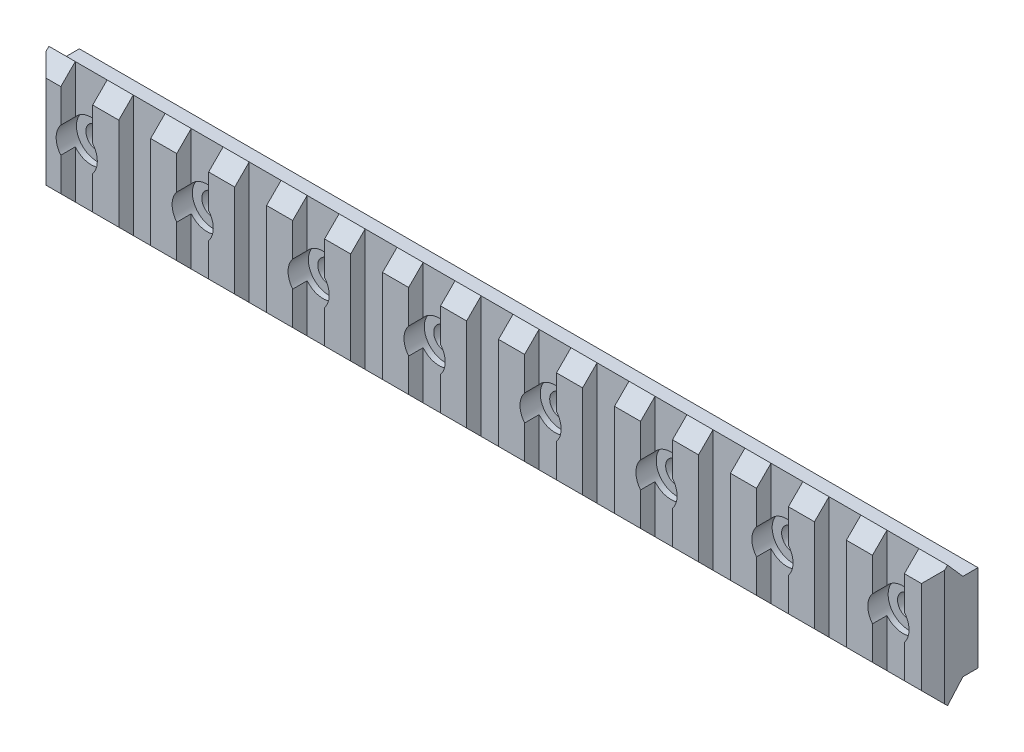
SolidWorks part; units mm, degrees
ref_plane "정면" through (0, 0, 0) normal (0, 0, 1) x (1, 0, 0)
ref_plane "윗면" through (0, 0, 0) normal (0, 1, 0) x (1, 0, 0)
ref_plane "우측면" through (0, 0, 0) normal (1, 0, 0) x (0, 0, -1)
sketch "스케치4" plane through (0, 0, 0) normal (1, 0, 0) x (0, 0, -1)
  line L0 (0, 7.5) -> (0, -7.5)
  line L1 (0, -7.5) -> (-2.6, -7.5)
  line L2 (-2.6, -7.5) -> (-5.25, -10.5)
  line L3 (-5.25, -10.5) -> (-7.75, -8)
  line L4 (-7.75, -8) -> (-7.75, 8)
  line L5 (-7.75, 0) -> (0, 0) construction
  line L6 (0, 0) -> (-0.1817, -0.0987)
  line L7 (0, 7.5) -> (-2.6, 7.5)
  line L8 (-2.6, 7.5) -> (-5.25, 10.5)
  line L9 (-5.25, 10.5) -> (-7.75, 8)
  dimension "D1" = 15
  dimension "D2" = 16
  dimension "D3" = 2.6
  dimension "D4" = 5.25
  dimension "D5" = 7.75
  dimension "D6" = 21
extrude "보스-돌출2" add sketch "스케치4" along normal blind 155 contours L5 L4 L3 L2 L1 L0 | L4 L5 L0 L1 L2 L3
chamfer "모따기1" distance 2 angle 45 2 edges at (0, 0, 7.75) (155, 0, 7.75)
sketch "스케치5" plane through (0, 0, 0) normal (0, 1, 0) x (1, 0, 0)
  line L0 (153, -7.75) -> (2, -7.75) construction
  line L1 (4.55, -7.75) -> (10.05, -7.75)
  line L2 (4.55, -7.75) -> (4.55, -5.25)
  line L3 (4.55, -5.25) -> (10.05, -5.25)
  line L4 (10.05, -7.75) -> (10.05, -5.25)
  line L5 (155, -5.25) -> (0, -5.25) construction
  dimension "D1" = 5.5
  dimension "D2" = 4.55
extrude "컷-돌출1" cut sketch "스케치5" against normal through all both and the other way through all
sketch "스케치6" plane through (0, 0, 5.25) normal (0, 0, 1) x (1, 0, 0)
  line L0 (7.3, 10.5) -> (7.3, -10.5) construction
  line L1 (10.05, 10.5) -> (4.55, 10.5) construction
  line L2 (10.05, -10.5) -> (4.55, -10.5) construction
  circle A0 centre (7.3, 0) radius 1.925
  dimension "D1" = 3.85
extrude "컷-돌출2" cut sketch "스케치6" against normal up to next
sketch "스케치7" plane through (0, 0, 7.75) normal (0, 0, 1) x (1, 0, 0)
  circle A0 centre (7.3, 0) radius 3.55
  dimension "D1" = 7.1
extrude "컷-돌출3" cut sketch "스케치7" against normal blind 3.5
pattern_linear "선형 패턴1" count 15 spacing 10 along (1, 0, 0) of "컷-돌출1"
pattern_linear "선형 패턴2" count 8 spacing 20 along (1, 0, 0) of "컷-돌출2", "컷-돌출3"
